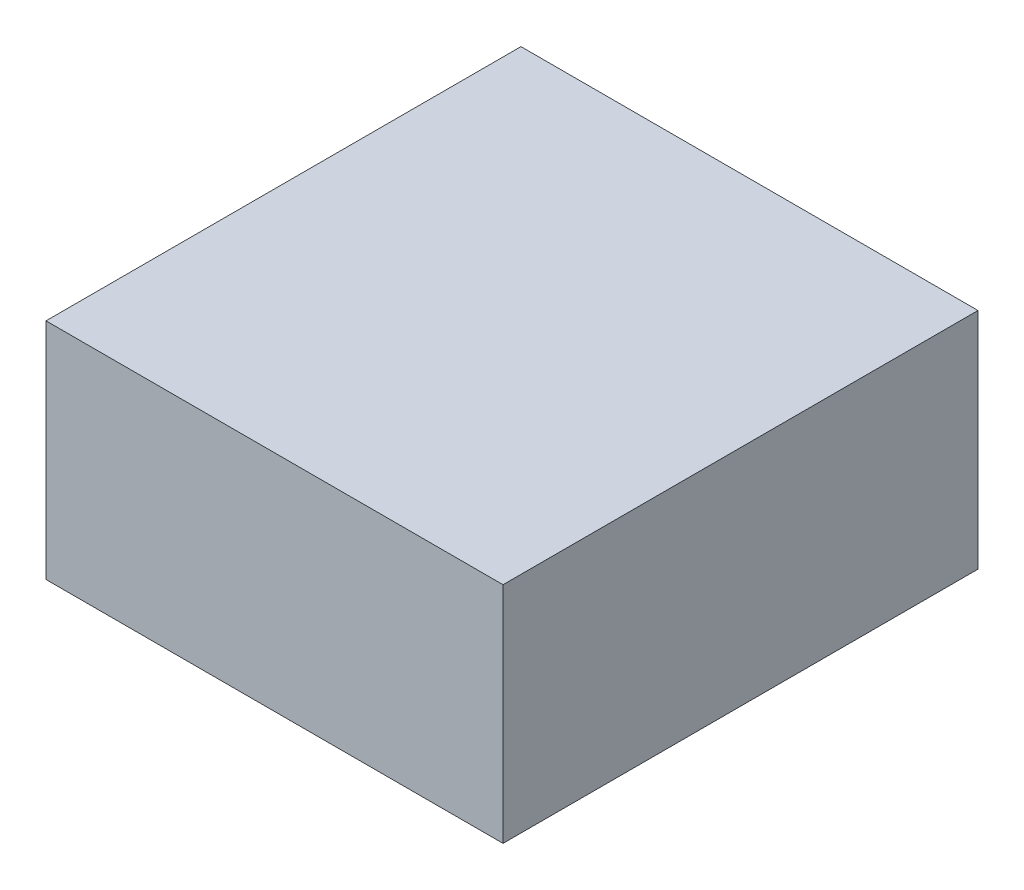
SolidWorks part; units mm, degrees
ref_plane "Plan de face" through (0, 0, 0) normal (0, 0, 1) x (1, 0, 0)
ref_plane "Plan de dessus" through (0, 0, 0) normal (0, 1, 0) x (1, 0, 0)
ref_plane "Plan de droite" through (0, 0, 0) normal (1, 0, 0) x (0, 0, -1)
sketch "Esquisse1" plane through (0, 0, 0) normal (0, 1, 0) x (1, 0, 0)
  line L1 (-25.5, 26.5) -> (25.5, 26.5)
  line L2 (-25.5, 26.5) -> (-25.5, -26.5)
  line L3 (-25.5, -26.5) -> (25.5, -26.5)
  line L4 (25.5, 26.5) -> (25.5, -26.5)
  point P4 (25.5, 0)
  point P6 (0, 26.5)
  dimension "D1" = 51
  dimension "D2" = 53
extrude "Boss.-Extru.1" add sketch "Esquisse1" along normal blind 25
